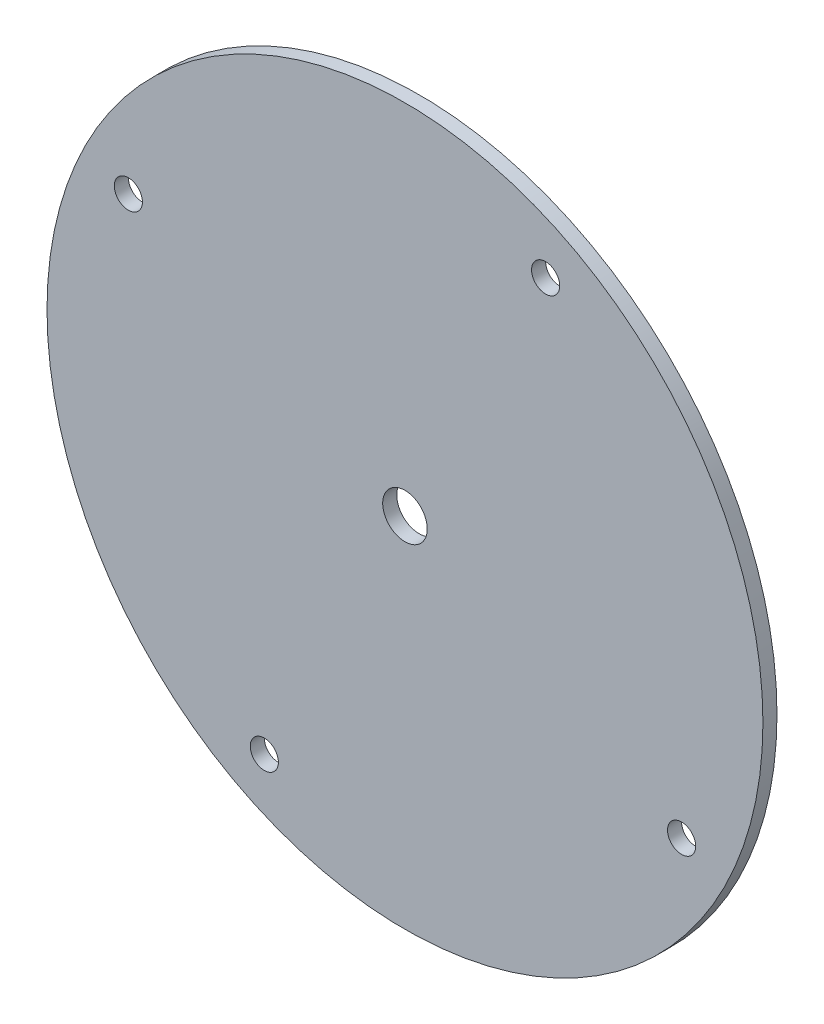
SolidWorks part; units mm, degrees
material "1060 Alloy"
ref_plane "Front Plane" through (0, 0, 0) normal (0, 0, 1) x (1, 0, 0)
ref_plane "Top Plane" through (0, 0, 0) normal (0, 1, 0) x (1, 0, 0)
ref_plane "Right Plane" through (0, 0, 0) normal (1, 0, 0) x (0, 0, -1)
sketch "Sketch1" plane through (0, 0, 0) normal (0, 0, 1) x (1, 0, 0)
  line L5 (50, -50) -> (-50, 50) construction
  line L6 (50, 50) -> (-50, -50) construction
  line L31 (24.5, 59) -> (27.25, 54.2369)
  line L32 (27.25, 54.2369) -> (32.75, 54.2369)
  line L33 (32.75, 54.2369) -> (35.5, 59)
  line L36 (-38.9, 50) -> (38.9, 50) construction
  line L50 (0, -76) -> (0, 122.6166) construction
  line L51 (-76, 0) -> (103.3867, 0) construction
  line L52 (35.5, 59) -> (32.75, 63.7631)
  line L53 (32.75, 63.7631) -> (27.25, 63.7631)
  line L54 (27.25, 63.7631) -> (24.5, 59)
  line L55 (-59, 24.5) -> (-54.2369, 27.25)
  line L56 (-54.2369, 27.25) -> (-54.2369, 32.75)
  line L57 (-54.2369, 32.75) -> (-59, 35.5)
  line L58 (-59, 35.5) -> (-63.7631, 32.75)
  line L59 (-63.7631, 32.75) -> (-63.7631, 27.25)
  line L60 (-63.7631, 27.25) -> (-59, 24.5)
  line L61 (59, -24.5) -> (54.2369, -27.25)
  line L62 (54.2369, -27.25) -> (54.2369, -32.75)
  line L96 (54.2369, -32.75) -> (59, -35.5)
  line L97 (59, -35.5) -> (63.7631, -32.75)
  line L98 (63.7631, -32.75) -> (63.7631, -27.25)
  line L99 (63.7631, -27.25) -> (59, -24.5)
  line L100 (-24.5, -59) -> (-27.25, -54.2369)
  line L101 (-27.25, -54.2369) -> (-32.75, -54.2369)
  line L102 (-32.75, -54.2369) -> (-35.5, -59)
  line L103 (-35.5, -59) -> (-32.75, -63.7631)
  line L104 (-32.75, -63.7631) -> (-27.25, -63.7631)
  line L105 (-27.25, -63.7631) -> (-24.5, -59)
  arc A0 (0, 76.35) -> (-72.3486, -24.3928) centre (0, 0) ccw
  circle A1 centre (30, 59) radius 3
  arc A2 (76.35, 0) -> (0, 76.35) centre (0, 0) ccw
  arc A3 (-72.3486, -24.3928) -> (0, -76.35) centre (0, 0) ccw
  arc A4 (0, -76.35) -> (76.35, 0) centre (0, 0) ccw
  circle A5 centre (59, -30) radius 3
  circle A6 centre (-30, -59) radius 3
  circle A7 centre (-59, 30) radius 3
  circle A8 centre (30, 59) radius 5.5 construction
  circle A9 centre (-59, 30) radius 5.5 construction
  circle A10 centre (59, -30) radius 5.5 construction
  circle A11 centre (-30, -59) radius 5.5 construction
  dimension "D1" = 152.7
  dimension "D9" = 30
  dimension "D2" = 59
  dimension "D15" = 11
  dimension "D16" = 11
  dimension "D17" = 11
  dimension "D3" = 30
  dimension "D4" = 59
  dimension "D5" = 59
  dimension "D6" = 59
  dimension "D10" = 30
  dimension "D11" = 30
extrude "Boss-Extrude3" add sketch "Sketch1" along normal blind 3
sketch "Sketch2" plane through (0, 0, 3) normal (0, 0, 1) x (1, 0, 0)
  circle A0 centre (0, 0) radius 4.75
  dimension "D1" = 9.5
extrude "Cut-Extrude1" cut sketch "Sketch2" against normal through all
